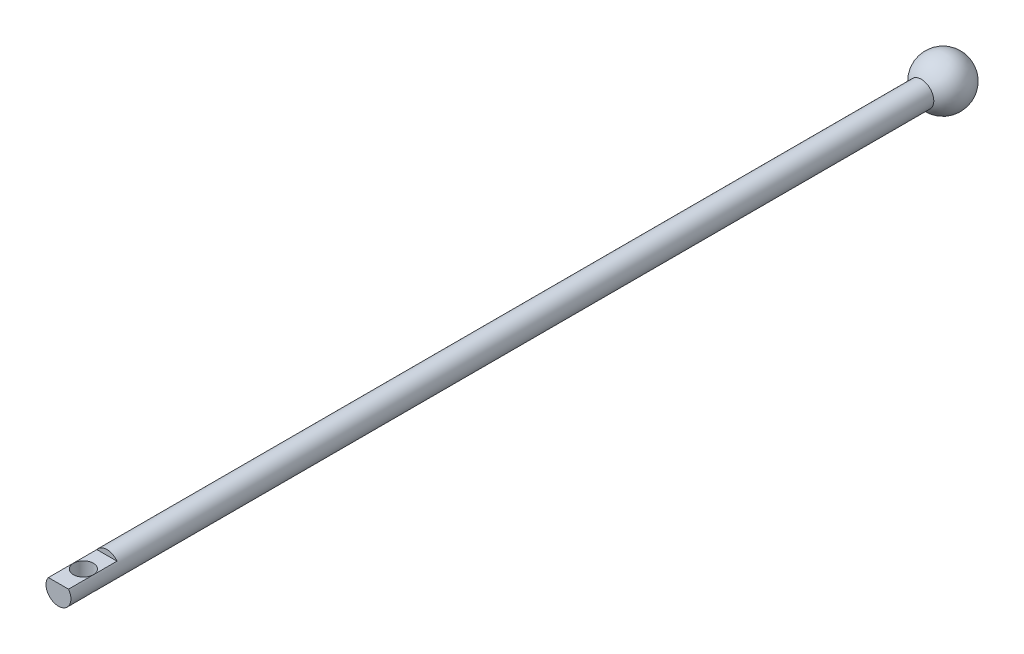
SolidWorks part; units mm, degrees
ref_plane "Front Plane" through (0, 0, 0) normal (0, 0, 1) x (1, 0, 0)
ref_plane "Top Plane" through (0, 0, 0) normal (0, 1, 0) x (1, 0, 0)
ref_plane "Right Plane" through (0, 0, 0) normal (1, 0, 0) x (0, 0, -1)
sketch "Sketch1" plane through (0, 0, 0) normal (0, 0, 1) x (1, 0, 0)
  circle A0 centre (-6.5044, -0.5897) radius 1
  dimension "D1" = 2
extrude "Boss-Extrude1" add sketch "Sketch1" along normal blind 70
ref_plane "Plane1" through (0, 0, -1) normal (0, 0, -1) x (-1, 0, 0)
sketch "Sketch2" plane through (0, 0, -1) normal (0, 0, -1) x (-1, 0, 0)
  line L0 (6.5044, 1.4103) -> (6.5044, -2.5897)
  line L1 (6.5044, 2.0476) -> (6.5044, -3.3296) construction
  arc A0 (6.5044, 1.4103) -> (6.5044, -2.5897) centre (6.5044, -0.5897) ccw
revolve "Revolve1" add sketch "Sketch2" angle 360 about L1
sketch "Sketch3" plane through (0, 0, 0) normal (0, 1, 0) x (1, 0, 0)
  line L1 (-8.4892, -66.1102) -> (-4.3307, -66.1102)
  line L2 (-8.4892, -66.1102) -> (-8.4892, -70.3853)
  line L3 (-8.4892, -70.3853) -> (-4.3307, -70.3853)
  line L4 (-4.3307, -66.1102) -> (-4.3307, -70.3853)
extrude "Cut-Extrude1" cut sketch "Sketch3" along normal blind 1
sketch "Sketch4" plane through (0, 0, 0) normal (0, 1, 0) x (1, 0, 0)
  line L0 (-5.5044, -70) -> (-5.5044, -0.7321) construction
  line L1 (-5.6968, -70) -> (-7.312, -70) construction
  circle A0 centre (-6.5044, -68) radius 0.8
  dimension "D1" = 1.6
  dimension "D2" = 1
  dimension "D3" = 2
extrude "Cut-Extrude2" cut sketch "Sketch4" against normal blind 4
